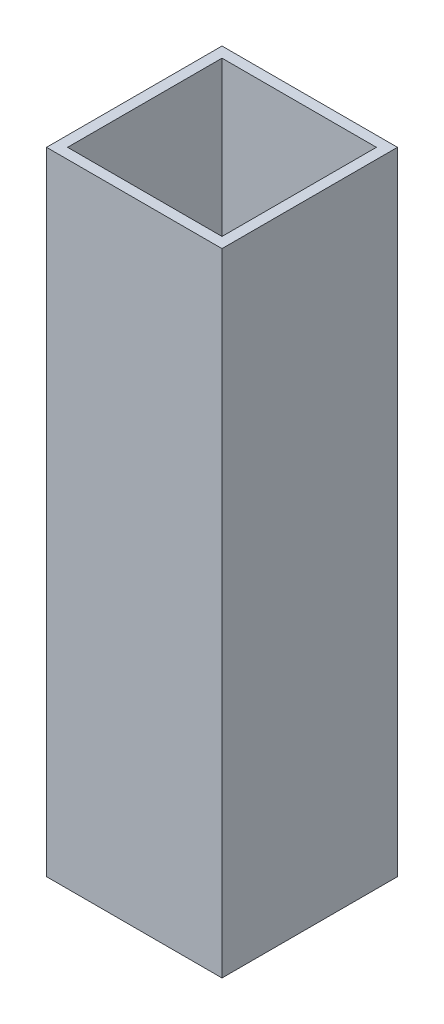
SolidWorks part; units mm, degrees
material "PE High Density"
ref_plane "Front Plane" through (0, 0, 0) normal (0, 0, 1) x (1, 0, 0)
ref_plane "Top Plane" through (0, 0, 0) normal (0, 1, 0) x (1, 0, 0)
ref_plane "Right Plane" through (0, 0, 0) normal (1, 0, 0) x (0, 0, -1)
sketch "Sketch1" plane through (0, 0, 0) normal (0, 1, 0) x (1, 0, 0)
  line L1 (-21.0084, 3.0987) -> (-8.5084, 3.0987)
  line L2 (-21.0084, 3.0987) -> (-21.0084, -9.4013)
  line L3 (-21.0084, -9.4013) -> (-8.5084, -9.4013)
  line L4 (-8.5084, 3.0987) -> (-8.5084, -9.4013)
  dimension "D1" = 12.5
  dimension "D2" = 12.5
extrude "Boss-Extrude1" add sketch "Sketch1" along normal blind 45
sketch "Sketch2" plane through (0, 45, 0) normal (0, 1, 0) x (1, 0, 0)
  line L1 (-20.2584, 2.3487) -> (-9.2584, 2.3487)
  line L2 (-20.2584, 2.3487) -> (-20.2584, -8.6513)
  line L3 (-20.2584, -8.6513) -> (-9.2584, -8.6513)
  line L4 (-9.2584, 2.3487) -> (-9.2584, -8.6513)
  line L8 (-8.5084, 3.0987) -> (-21.0084, 3.0987) construction
  line L10 (-21.0084, 3.0987) -> (-21.0084, -9.4013) construction
  dimension "D1" = 0.75
  dimension "D2" = 0.75
extrude "Cut-Extrude2" cut sketch "Sketch2" against normal blind 44
